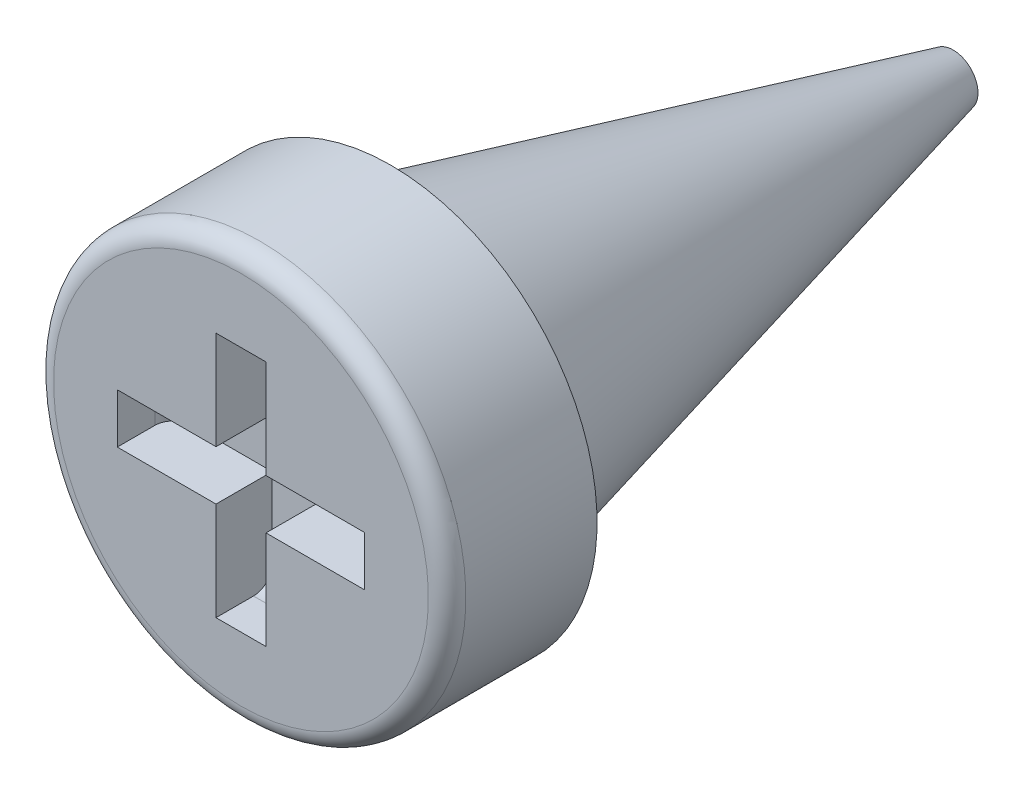
SolidWorks part; units mm, degrees
ref_plane "Plan de face" through (0, 0, 0) normal (0, 0, 1) x (1, 0, 0)
ref_plane "Plan de dessus" through (0, 0, 0) normal (0, 1, 0) x (1, 0, 0)
ref_plane "Plan de droite" through (0, 0, 0) normal (1, 0, 0) x (0, 0, -1)
sketch "Esquisse1" plane through (0, 0, 0) normal (1, 0, 0) x (0, 0, -1)
  line L0 (9.12, 0) -> (0, 0)
  line L1 (0, 0) -> (0, 2.4)
  line L2 (0.24, 2.64) -> (1.92, 2.64)
  line L3 (1.92, 2.64) -> (1.92, 2.1132)
  line L4 (1.92, 2.1132) -> (9.12, 0.318)
  line L5 (9.12, 0.318) -> (9.12, 0)
  line L6 (1.92, 2.64) -> (11.0236, 2.64) construction
  arc A0 (0, 2.4) -> (0.24, 2.64) centre (0.24, 2.4) cw
  point P3 (9.12, 0.159)
  dimension "D3" = 0.24
  dimension "D1" = 1.92
  dimension "D2" = 7.2
  dimension "D4" = 0.318
  dimension "D5" = 14
  dimension "D6" = 2.4
revolve "Révolution1" add sketch "Esquisse1" angle 360 about L0
sketch "Esquisse3" plane through (0, 0, 0) normal (0, 0, 1) x (1, 0, 0)
  line L0 (0, 1.3895) -> (0, -1.8095) construction
  line L1 (-1.68, 0) -> (2.1279, 0) construction
  line L2 (0.32, 1.578) -> (-0.32, 1.578)
  line L3 (-0.32, 1.578) -> (-0.32, 0.318)
  line L4 (-0.32, 0.318) -> (-1.584, 0.318)
  line L5 (-1.584, 0.318) -> (-1.584, -0.318)
  line L6 (1.584, 0.318) -> (1.584, -0.318)
  line L7 (0.32, 0.318) -> (1.584, 0.318)
  line L8 (0.32, 1.578) -> (0.32, 0.318)
  line L9 (0.32, -0.318) -> (1.584, -0.318)
  line L10 (0.32, -1.578) -> (0.32, -0.318)
  line L11 (0.32, -1.578) -> (-0.32, -1.578)
  line L12 (-0.32, -1.578) -> (-0.32, -0.318)
  line L13 (-0.32, -0.318) -> (-1.584, -0.318)
  point P14 (0, 1.578)
  point P15 (1.584, 0)
  point P20 (-1.584, 0)
  dimension "D1" = 0.318
  dimension "D2" = 1.584
  dimension "D3" = 0.32
  dimension "D4" = 1.26
extrude "Enlèv. mat.-Extru.2" cut sketch "Esquisse3" against normal blind 0.72
fillet "Congé4" radius 0.24 4 edges at (0, -1.578, -0.72) (1.584, 0, -0.72) (0, 1.578, -0.72) (-1.584, 0, -0.72)
